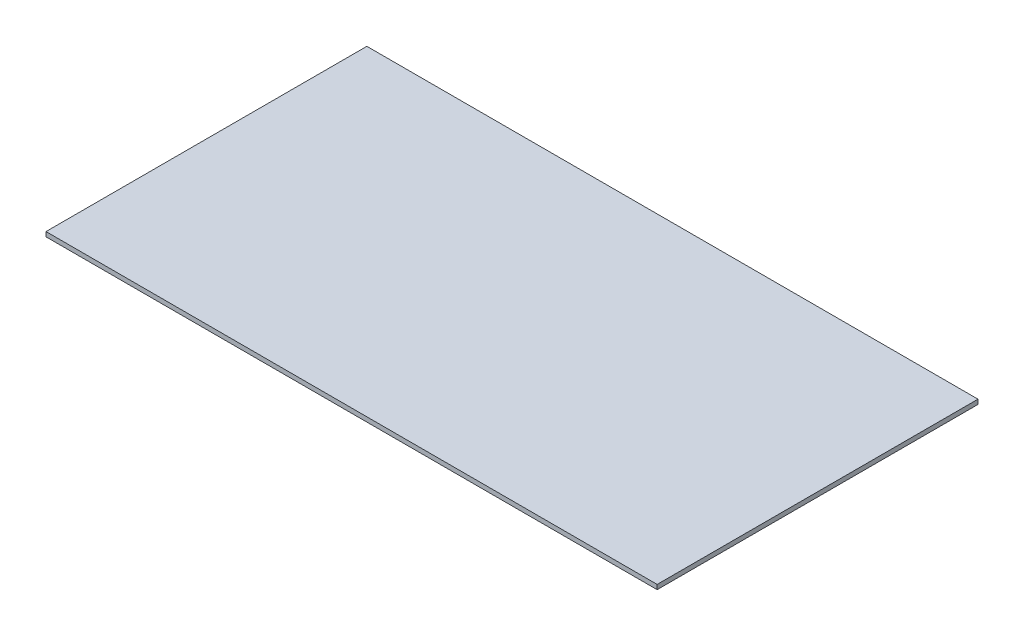
SolidWorks part; units mm, degrees
ref_plane "Front Plane" through (0, 0, 0) normal (0, 0, 1) x (1, 0, 0)
ref_plane "Top Plane" through (0, 0, 0) normal (0, 1, 0) x (1, 0, 0)
ref_plane "Right Plane" through (0, 0, 0) normal (1, 0, 0) x (0, 0, -1)
sketch "Sketch1" plane through (0, 0, 0) normal (0, 1, 0) x (1, 0, 0)
  line L1 (0, 0) -> (400, 0)
  line L2 (0, 0) -> (0, -210)
  line L3 (0, -210) -> (400, -210)
  line L4 (400, 0) -> (400, -210)
  dimension "D1" = 400
  dimension "D2" = 210
extrude "Boss-Extrude1" add sketch "Sketch1" along normal blind 3
